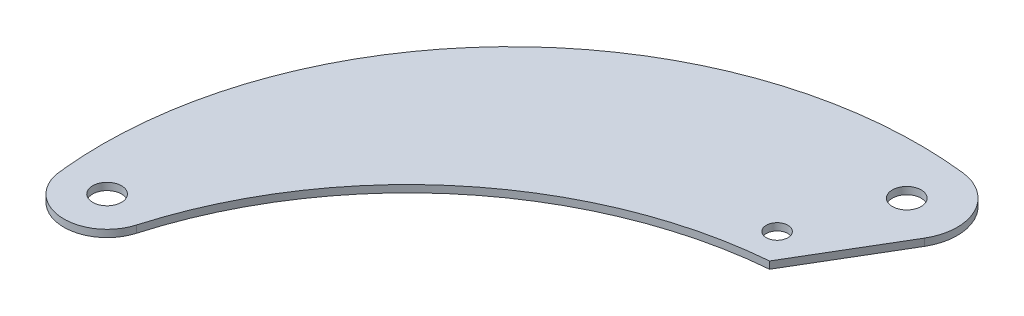
SolidWorks part; units mm, degrees
ref_plane "Front Plane" through (0, 0, 0) normal (0, 0, 1) x (1, 0, 0)
ref_plane "Top Plane" through (0, 0, 0) normal (0, 1, 0) x (1, 0, 0)
ref_plane "Right Plane" through (0, 0, 0) normal (1, 0, 0) x (0, 0, -1)
sketch "Sketch1" plane through (0, 0, 0) normal (0, 1, 0) x (1, 0, 0)
  line L1 (-564.005, -56.387) -> (-563.6702, -56.387) construction
  line L3 (116.5502, 457.9268) -> (36.5502, 322.9268)
  arc A2 (116.5502, 457.9268) -> (64.2665, 563.1616) centre (56.3298, 493.613) ccw
  circle A3 centre (56.3298, 493.613) radius 20
  arc A4 (-563.6702, -56.387) -> (-446.0121, -72.9866) centre (-503.6702, -56.387) ccw
  arc A5 (36.5502, 322.9268) -> (-446.0121, -72.9866) centre (82.5205, -225.1487) ccw
  circle A6 centre (-503.6702, -56.387) radius 20
  circle A7 centre (6.3298, 363.613) radius 15
  arc A8 (64.2665, 563.1616) -> (-563.2977, -63.0625) centre (0, 0) ccw
  point P6 (0, 0)
  dimension "D1" = 1100
  dimension "D2" = 140
  dimension "D3" = 40
  dimension "D6" = 80
  dimension "D8" = 120
  dimension "D11" = 30
  dimension "D5" = 550
  dimension "D7" = 135
extrude "Boss-Extrude1" add sketch "Sketch1" along normal mid plane 10 contours A8 L1 A4 A5 L3 A2 A3 A6 A7
